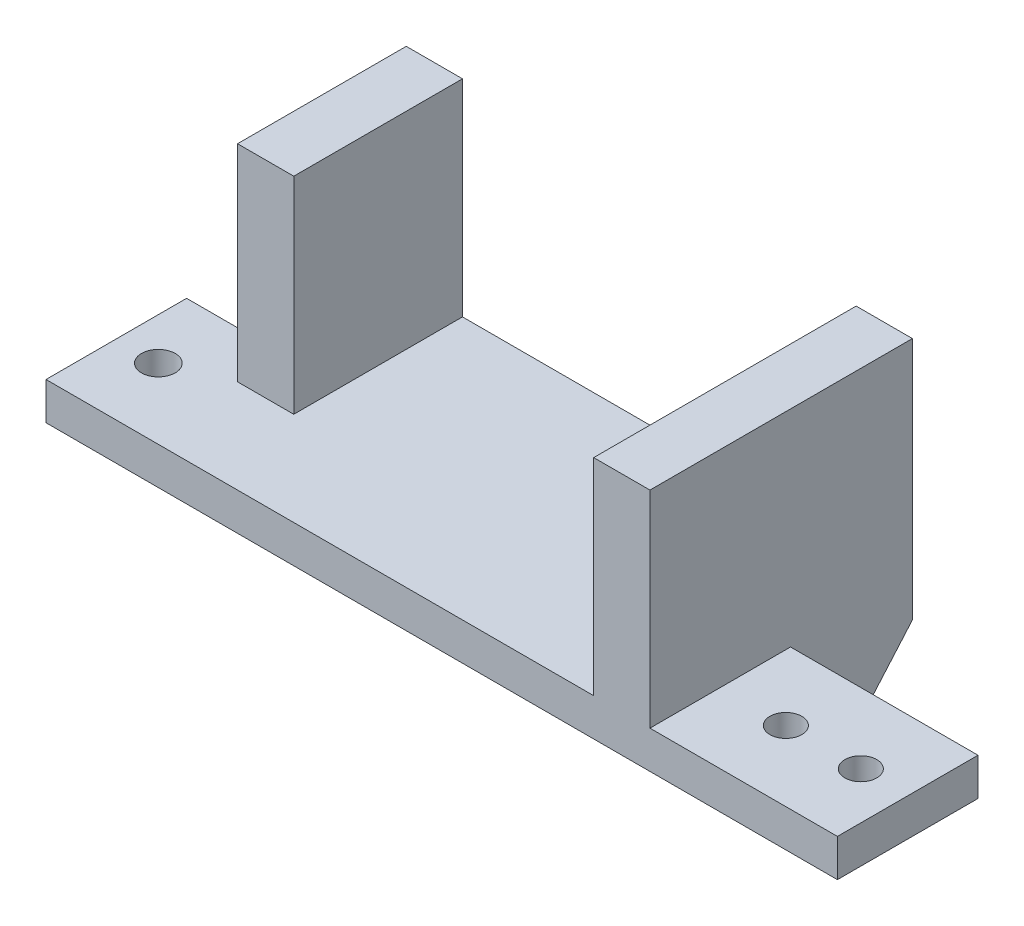
SolidWorks part; units mm, degrees
ref_plane "Front" through (0, 0, 0) normal (0, 0, 1) x (1, 0, 0)
ref_plane "Top" through (0, 0, 0) normal (0, 1, 0) x (1, 0, 0)
ref_plane "Right" through (0, 0, 0) normal (1, 0, 0) x (0, 0, -1)
sketch "Sketch1" plane through (0, 0, 0) normal (0, 0, 1) x (1, 0, 0)
  line L0 (-21, 0) -> (21, 0)
  line L1 (21, 0) -> (21, 26)
  line L2 (21, 26) -> (27, 26)
  line L3 (27, 26) -> (27, 4)
  line L4 (27, 4) -> (47, 4)
  line L5 (47, 4) -> (47, 0)
  line L6 (47, 0) -> (21, 0)
  line L7 (21, 4) -> (-21, 4)
  line L8 (0, 4) -> (0, 0)
  line L9 (-47, 0) -> (-21, 0)
  line L10 (-47, 4) -> (-47, 0)
  line L11 (-27, 4) -> (-47, 4)
  line L12 (-27, 26) -> (-27, 4)
  line L13 (-21, 26) -> (-27, 26)
  line L14 (-21, 0) -> (-21, 26)
  point P4 (0, 0)
  point P19 (24, 26)
  point P20 (-24, 26)
  dimension "D1" = 4
  dimension "D2" = 6
  dimension "D3" = 26
  dimension "D4" = 20
  dimension "D5" = 48
  dimension "D6" = 0
extrude "Boss-Extrude1" add sketch "Sketch1" along normal blind 15 contours L6 L5 L4 L3 L2 L1 | L14 L0 L8 L7 | L7 L8 L0 L1 | L9 L14 L13 L12 L11 L10
sketch "Sketch2" plane through (0, 0, 0) normal (0, 0, -1) x (-1, 0, 0)
  line L0 (-27, 26) -> (-27, 0)
  line L1 (-47, 0) -> (47, 0) construction
  line L2 (-27, 26) -> (-21, 26)
  line L3 (-21, 26) -> (-27, 26) construction
  line L4 (-21, 26) -> (-21, 4)
  line L5 (-21, 4) -> (21, 4)
  line L6 (21, 4) -> (21, 26)
  line L7 (21, 26) -> (27, 26)
  line L8 (27, 26) -> (27, 4)
  line L9 (27, 4) -> (27, 0)
  line L10 (27, 0) -> (-27, 0)
extrude "Boss-Extrude2" add sketch "Sketch2" along normal blind 13
sketch "Sketch3" plane through (0, 0, -13) normal (0, 0, -1) x (-1, 0, 0)
  line L0 (-24, 26) -> (-24, 6)
  line L2 (-21, 26) -> (-27, 26) construction
  line L3 (24, 26) -> (24, 6)
  line L5 (27, 26) -> (21, 26) construction
  line L6 (-24, 20.95) -> (-24, 11.05)
  line L7 (24, 20.95) -> (24, 11.05)
  circle A0 centre (-24, 20.95) radius 1.8
  circle A1 centre (-24, 11.05) radius 1.8
  circle A2 centre (24, 20.95) radius 1.8
  circle A3 centre (24, 11.05) radius 1.8
  point P11 (-24, 16)
  point P14 (24, 16)
  dimension "D1" = 20
  dimension "D2" = 20
  dimension "D3" = 9.9
  dimension "D4" = 9.9
extrude "Cut-Extrude1" cut sketch "Sketch3" against normal blind 10 contours L0 A0 | A1 | A2 | A3
sketch "Sketch4" plane through (0, 4, 0) normal (0, 1, 0) x (1, 0, 0)
  line L4 (47, -7.5) -> (42, -7.5)
  line L5 (47, -15) -> (47, 0) construction
  line L6 (42, -7.5) -> (34, -7.5)
  line L7 (-27, 0) -> (-47, 0) construction
  line L8 (-47, -15) -> (-37.4348, -15)
  line L9 (-47, -15) -> (-47, 0)
  line L10 (-47, 0) -> (-37.4348, 0)
  line L11 (-37.4348, -15) -> (-37.4348, 0)
  line L12 (27, 0) -> (47, 0) construction
  circle A0 centre (42, -7.5) radius 1.7
  circle A1 centre (34, -7.5) radius 1.7
  circle A2 centre (-32.9498, -7.5) radius 1.8
  line M3 (-27, 0) -> (-47, 0)
  line M4 (-47, 0) -> (-47, -15)
  line M5 (-47, -15) -> (-27, -15)
  dimension "D3" = 7.5
  dimension "D1" = 5
  dimension "D2" = 8
  dimension "D4" = 7.5
extrude "Cut-Extrude2" cut sketch "Sketch4" against normal blind 15 contours L11 M5 M3 M4 | A2 | A0 | A1
sketch "Sketch5" plane through (0, 26, 0) normal (0, 1, 0) x (1, 0, 0)
  line L0 (-27, -15) -> (-27, -5)
  line L1 (-27, -15) -> (-27, 13) construction
  line L2 (-27, -5) -> (-21, -5)
  line L3 (-21, -15) -> (-21, 13) construction
  line L4 (-21, -5) -> (-21, -15)
  line L5 (-21, -15) -> (-27, -15)
  dimension "D1" = 10
extrude "Cut-Extrude3" cut sketch "Sketch5" against normal blind 22
sketch "Sketch6" plane through (-27, 0, 0) normal (-1, 0, 0) x (0, 0, 1)
  line L0 (-13, 0) -> (0, 0)
  line L1 (-13, 0) -> (0, 0) construction
  line L2 (0, 0) -> (0, -15)
  line L3 (0, -15) -> (-13, 0)
  line L4 (15, 4) -> (15, 0) construction
  dimension "D1" = 15
  dimension "D2" = 15
extrude "Boss-Extrude3" add sketch "Sketch6" against normal blind 54
sketch "Sketch7" plane through (0, 0, -13) normal (0, 0, -1) x (-1, 0, 0)
  line L0 (-21, 0) -> (-21, -15)
  line L1 (-27, 0) -> (27, 0) construction
  line L2 (-21, -15) -> (-3, -15)
  line L3 (-3, -15) -> (-3, 0)
  line L4 (-3, 0) -> (-21, 0)
  line L5 (3, 0) -> (3, -15)
  line L6 (3, -15) -> (21, -15)
  line L7 (21, -15) -> (21, 0)
  line L8 (21, 0) -> (3, 0)
  line L9 (-27, 0) -> (-27, -15) construction
  line L10 (27, 0) -> (27, -15) construction
  line L11 (-3, -15) -> (3, -15)
  line L12 (-21, 4) -> (21, 4)
  point P14 (0, -15)
  point P19 (0, 4)
  line M11 (-27, 0) -> (27, 0)
  dimension "D1" = 6
  dimension "D2" = 6
  dimension "D3" = 6
  dimension "D4" = 15
  dimension "D5" = 15
  dimension "D6" = 0
extrude "Cut-Extrude4" cut sketch "Sketch7" against normal blind 11 contours L2 L3 L0 M11 | L6 L7 L5 M11
